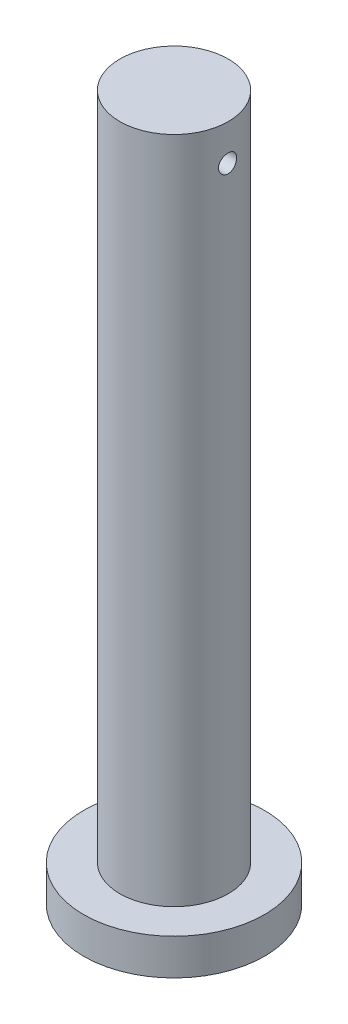
SolidWorks part; units mm, degrees
ref_plane "Front Plane" through (0, 0, 0) normal (0, 0, 1) x (1, 0, 0)
ref_plane "Top Plane" through (0, 0, 0) normal (0, 1, 0) x (1, 0, 0)
ref_plane "Right Plane" through (0, 0, 0) normal (1, 0, 0) x (0, 0, -1)
sketch "Sketch1" plane through (0, 0, 0) normal (0, 1, 0) x (1, 0, 0)
  circle A0 centre (0, 0) radius 25
  dimension "D1" = 50
extrude "Boss-Extrude1" add sketch "Sketch1" along normal blind 10
sketch "Sketch2" plane through (0, 10, 0) normal (0, 1, 0) x (1, 0, 0)
  circle A0 centre (0, 0) radius 15
  dimension "D1" = 30
extrude "Boss-Extrude2" add sketch "Sketch2" along normal blind 185
sketch "Sketch3" plane through (0, 0, 0) normal (1, 0, 0) x (0, 0, -1)
  line L0 (15, 195) -> (-15, 195) construction
  circle A0 centre (0, 185) radius 2.5
  point P2 (0, 0)
  dimension "D1" = 5
  dimension "D2" = 10
extrude "Cut-Extrude1" cut sketch "Sketch3" against normal mid plane 185
